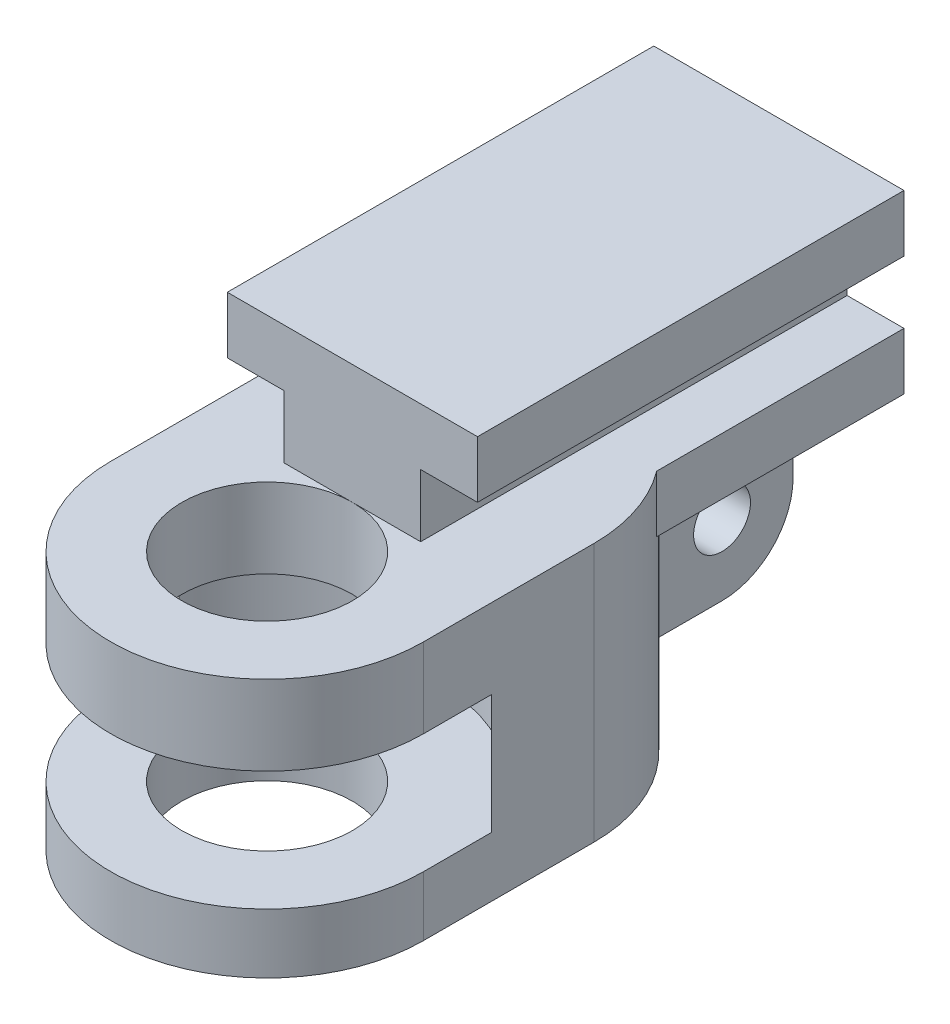
SolidWorks part; units mm, degrees
ref_plane "Front Plane" through (0, 0, 0) normal (0, 0, 1) x (1, 0, 0)
ref_plane "Top Plane" through (0, 0, 0) normal (0, 1, 0) x (1, 0, 0)
ref_plane "Right Plane" through (0, 0, 0) normal (1, 0, 0) x (0, 0, -1)
sketch "Sketch1" plane through (0, 0, 0) normal (0, 0, 1) x (1, 0, 0)
  line L0 (0, 0) -> (-2.4, 0) construction
  line L1 (-2.4, -1.1) -> (-2.4, 1.1)
  line L2 (-2.4, 1.1) -> (-4.4, 1.1)
  line L3 (-4.4, 1.1) -> (-4.4, 3.1)
  line L4 (-4.4, 3.1) -> (4.4, 3.1)
  line L5 (4.4, 1.1) -> (4.4, 3.1)
  line L6 (2.4, 1.1) -> (4.4, 1.1)
  line L7 (2.4, -1.1) -> (2.4, 1.1)
  line L8 (0, 0) -> (0, 3.1) construction
  line L9 (2.4, -1.1) -> (4.4, -1.1)
  line L10 (4.4, -1.1) -> (4.4, -3.1)
  line L11 (-4.4, -3.1) -> (4.4, -3.1)
  line L12 (-4.4, -1.1) -> (-4.4, -3.1)
  line L13 (-2.4, -1.1) -> (-4.4, -1.1)
  point P13 (2.4, 0)
  dimension "D1" = 1.1
  dimension "D2" = 2
  dimension "D3" = 2
  dimension "D4" = 2.4
extrude "Boss-Extrude1" add sketch "Sketch1" along normal blind 15
sketch "Sketch3" plane through (0, 0, 0) normal (0, 1, 0) x (1, 0, 0)
  line L0 (0, -18) -> (0, -12) construction
  line L1 (-5.5, -18) -> (-5.5, -12)
  line L2 (5.5, -18) -> (5.5, -12)
  circle A0 centre (0, -18) radius 3
  arc A1 (-5.5, -18) -> (5.5, -18) centre (0, -18) ccw
  arc A2 (5.5, -12) -> (-5.5, -12) centre (0, -12) ccw
  point P2 (0, -15)
  dimension "D1" = 6
  dimension "D2" = 2.5
  dimension "D3" = 18
  dimension "D4" = 6
sketch "Sketch5" plane through (0, -1.1, 0) normal (0, 1, 0) x (1, 0, 0)
  line L0 (5.5, -18) -> (5.5, -12) construction
  line L1 (-5.5, -18) -> (-5.5, -12) construction
  line L2 (5.5, -18) -> (5.5, -12)
  line L3 (-5.5, -18) -> (-5.5, -12)
  circle A0 centre (0, -18) radius 3 construction
  arc A1 (5.5, -12) -> (-5.5, -12) centre (0, -12) ccw construction
  arc A2 (-5.5, -18) -> (5.5, -18) centre (0, -18) ccw construction
  circle A3 centre (0, -18) radius 3
  arc A4 (5.5, -12) -> (-5.5, -12) centre (0, -12) ccw
  arc A5 (-5.5, -18) -> (5.5, -18) centre (0, -18) ccw
extrude "Boss-Extrude3" add sketch "Sketch5" against normal blind 9.1
ref_plane "Plane1" through (0, -8.1, 0) normal (0, -1, 0) x (-1, 0, 0)
sketch "Sketch6" plane through (0, -8.1, 0) normal (0, -1, 0) x (-1, 0, 0)
  circle A0 centre (0, -18) radius 6
  dimension "D1" = 12
extrude "Cut-Extrude1" cut sketch "Sketch6" against normal blind 4.2
sketch "Sketch7" plane through (0, 0, 0) normal (1, 0, 0) x (0, 0, -1)
  line L0 (-3.5, -6.6) -> (-6.5, -6.6) construction
  line L1 (-6.5, -10.2) -> (-6.5, -3.1) construction
  line L2 (-3.5, -9.1) -> (-6.5, -9.1)
  line L4 (-1, -6.6) -> (-1, -3.1)
  line L5 (-8.7, -3.1) -> (0, -3.1) construction
  line L7 (-6.5, -9.1) -> (-9.5, -9.1)
  line L8 (-9.5, -9.1) -> (-9.5, -3.1)
  line L9 (-9.5, -3.1) -> (-1, -3.1)
  circle A0 centre (-3.5, -6.6) radius 1
  arc A1 (-3.5, -9.1) -> (-1, -6.6) centre (-3.5, -6.6) ccw
  point P6 (-5, -6.6)
  dimension "D1" = 2
  dimension "D4" = 2.5
  dimension "D2" = 6
  dimension "D3" = 3
  dimension "D5" = 3
extrude "Boss-Extrude4" add sketch "Sketch7" along normal blind 1.5 and the other way blind 1.5
